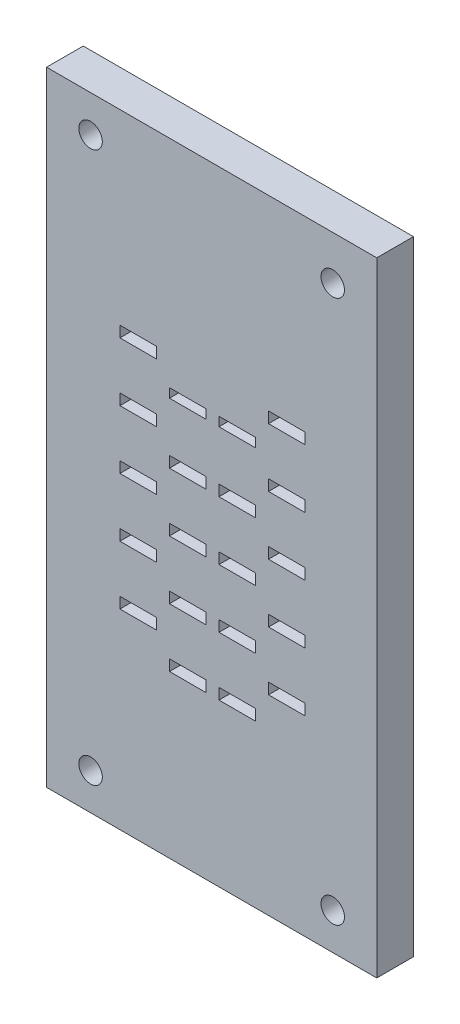
SolidWorks part; units mm, degrees
ref_plane "Ebene vorne" through (0, 0, 0) normal (0, 0, 1) x (1, 0, 0)
ref_plane "Ebene oben" through (0, 0, 0) normal (0, 1, 0) x (1, 0, 0)
ref_plane "Ebene rechts" through (0, 0, 0) normal (1, 0, 0) x (0, 0, -1)
sketch "Skizze1" plane through (0, 0, 0) normal (0, 0, 1) x (1, 0, 0)
  line L1 (0, 0) -> (45, 0)
  line L2 (0, 0) -> (0, 85)
  line L3 (0, 85) -> (45, 85)
  line L4 (45, 0) -> (45, 85)
  dimension "D1" = 45
  dimension "D2" = 85
extrude "Aufsatz-Linear austragen1" add sketch "Skizze1" along normal blind 5
sketch "Skizze3" plane through (0, 0, 5) normal (0, 0, 1) x (1, 0, 0)
  line L0 (0, 85) -> (0, 0) construction
  line L1 (10, 59.55) -> (15, 59.55)
  line L2 (10, 59.55) -> (10, 58.05)
  line L3 (10, 58.05) -> (15, 58.05)
  line L4 (15, 59.55) -> (15, 58.05)
  line L5 (30.25, 59.55) -> (35.25, 59.55)
  line L6 (30.25, 59.55) -> (30.25, 58.05)
  line L7 (30.25, 58.05) -> (35.25, 58.05)
  line L8 (35.25, 59.55) -> (35.25, 58.05)
  line L10 (45, 85) -> (0, 85) construction
  line L11 (16.75, 47.55) -> (21.75, 47.55)
  line L12 (10, 51.55) -> (15, 51.55)
  line L13 (10, 51.55) -> (10, 50.05)
  line L14 (10, 50.05) -> (15, 50.05)
  line L15 (15, 51.55) -> (15, 50.05)
  line L16 (30.25, 51.55) -> (35.25, 51.55)
  line L17 (30.25, 51.55) -> (30.25, 50.05)
  line L18 (30.25, 50.05) -> (35.25, 50.05)
  line L19 (35.25, 51.55) -> (35.25, 50.05)
  line L20 (10, 43.55) -> (15, 43.55)
  line L21 (10, 43.55) -> (10, 42.05)
  line L22 (10, 42.05) -> (15, 42.05)
  line L23 (15, 43.55) -> (15, 42.05)
  line L24 (30.25, 42.05) -> (35.25, 42.05)
  line L25 (30.25, 42.05) -> (30.25, 43.55)
  line L26 (30.25, 43.55) -> (35.25, 43.55)
  line L27 (35.25, 42.05) -> (35.25, 43.55)
  line L28 (10, 35.55) -> (15, 35.55)
  line L29 (10, 35.55) -> (10, 34.05)
  line L30 (10, 34.05) -> (15, 34.05)
  line L31 (15, 35.55) -> (15, 34.05)
  line L32 (30.25, 34.05) -> (35.25, 34.05)
  line L33 (30.25, 34.05) -> (30.25, 35.55)
  line L34 (30.25, 35.55) -> (35.25, 35.55)
  line L35 (35.25, 34.05) -> (35.25, 35.55)
  line L36 (35.25, 27.55) -> (30.25, 27.55)
  line L37 (35.25, 27.55) -> (35.25, 26.05)
  line L38 (35.25, 26.05) -> (30.25, 26.05)
  line L39 (30.25, 27.55) -> (30.25, 26.05)
  line L40 (15, 26.05) -> (10, 26.05)
  line L41 (15, 26.05) -> (15, 27.55)
  line L42 (15, 27.55) -> (10, 27.55)
  line L43 (10, 26.05) -> (10, 27.55)
  line L44 (16.75, 47.55) -> (16.75, 46.05)
  line L45 (16.75, 55.55) -> (21.75, 55.55)
  line L46 (16.75, 55.55) -> (16.75, 54.3081)
  line L47 (16.75, 54.3081) -> (21.75, 54.3081)
  line L48 (21.75, 55.55) -> (21.75, 54.3081)
  line L49 (23.5, 54.3081) -> (28.5, 54.3081)
  line L50 (23.5, 54.3081) -> (23.5, 55.55)
  line L51 (23.5, 55.55) -> (28.5, 55.55)
  line L52 (28.5, 54.3081) -> (28.5, 55.55)
  line L53 (16.75, 46.05) -> (21.75, 46.05)
  line L54 (21.75, 47.55) -> (21.75, 46.05)
  line L55 (23.5, 46.05) -> (28.5, 46.05)
  line L56 (23.5, 46.05) -> (23.5, 47.55)
  line L57 (23.5, 47.55) -> (28.5, 47.55)
  line L58 (28.5, 46.05) -> (28.5, 47.55)
  line L59 (28.5, 39.55) -> (23.5, 39.55)
  line L60 (28.5, 39.55) -> (28.5, 38.05)
  line L61 (28.5, 38.05) -> (23.5, 38.05)
  line L62 (23.5, 39.55) -> (23.5, 38.05)
  line L63 (21.75, 38.05) -> (16.75, 38.05)
  line L64 (21.75, 38.05) -> (21.75, 39.55)
  line L65 (21.75, 39.55) -> (16.75, 39.55)
  line L66 (16.75, 38.05) -> (16.75, 39.55)
  line L67 (16.75, 31.55) -> (21.75, 31.55)
  line L68 (16.75, 31.55) -> (16.75, 30.05)
  line L69 (16.75, 30.05) -> (21.75, 30.05)
  line L70 (21.75, 31.55) -> (21.75, 30.05)
  line L71 (23.5, 30.05) -> (28.5, 30.05)
  line L72 (23.5, 30.05) -> (23.5, 31.55)
  line L73 (23.5, 31.55) -> (28.5, 31.55)
  line L74 (28.5, 30.05) -> (28.5, 31.55)
  line L75 (28.5, 23.55) -> (23.5, 23.55)
  line L76 (28.5, 23.55) -> (28.5, 22.05)
  line L77 (28.5, 22.05) -> (23.5, 22.05)
  line L78 (23.5, 23.55) -> (23.5, 22.05)
  line L79 (21.75, 22.05) -> (16.75, 22.05)
  line L80 (21.75, 22.05) -> (21.75, 23.55)
  line L81 (21.75, 23.55) -> (16.75, 23.55)
  line L82 (16.75, 22.05) -> (16.75, 23.55)
  dimension "D1" = 10
  dimension "D2" = 5
  dimension "D3" = 5
  dimension "D4" = 15.25
  dimension "D5" = 1.5
  dimension "D6" = 1.5
  dimension "D7" = 25.45
  dimension "D8" = 6.5
  dimension "D9" = 6.5
  dimension "D10" = 6.5
  dimension "D11" = 1.5
  dimension "D12" = 1.5
  dimension "D13" = 6.5
  dimension "D14" = 1.5
  dimension "D15" = 1.5
  dimension "D16" = 6.5
  dimension "D17" = 6.5
  dimension "D18" = 6.5
  dimension "D19" = 6.5
  dimension "D20" = 1.5
  dimension "D21" = 1.5
  dimension "D22" = 1.5
  dimension "D23" = 1.5
  dimension "D24" = 5
  dimension "D25" = 5
  dimension "D26" = 1.75
  dimension "D27" = 1.75
  dimension "D28" = 2.5
  dimension "D29" = 2.5
  dimension "D30" = 2.5
  dimension "D31" = 2.5
  dimension "D32" = 2.5
  dimension "D33" = 2.5
  dimension "D34" = 2.5
  dimension "D35" = 2.5
  dimension "D36" = 2.5
  dimension "D37" = 2.5
  dimension "D38" = 1.5
  dimension "D39" = 1.5
  dimension "D40" = 1.5
  dimension "D41" = 1.5
  dimension "D42" = 1.5
  dimension "D43" = 1.5
  dimension "D44" = 1.5
  dimension "D45" = 1.5
extrude "Schnitt-Linear austragen1" cut sketch "Skizze3" against normal blind 5
sketch "Skizze4" plane through (0, 0, 5) normal (0, 0, 1) x (1, 0, 0)
  line L0 (45, 85) -> (0, 85) construction
  line L1 (0, 85) -> (0, 0) construction
  line L2 (45, 0) -> (45, 85) construction
  line L3 (0, 0) -> (45, 0) construction
  circle A0 centre (6, 80) radius 1.6
  circle A1 centre (39, 79) radius 1.6
  circle A2 centre (39, 5) radius 1.6
  circle A3 centre (6, 5) radius 1.6
  dimension "D1" = 5
  dimension "D2" = 6
  dimension "D3" = 6
  dimension "D4" = 6
  dimension "D5" = 5
  dimension "D6" = 6
  dimension "D7" = 5
  dimension "D8" = 6
  dimension "D9" = 3.2
  dimension "D10" = 3.2
  dimension "D11" = 3.2
  dimension "D12" = 3.2
extrude "Schnitt-Linear austragen2" cut sketch "Skizze4" against normal blind 5
